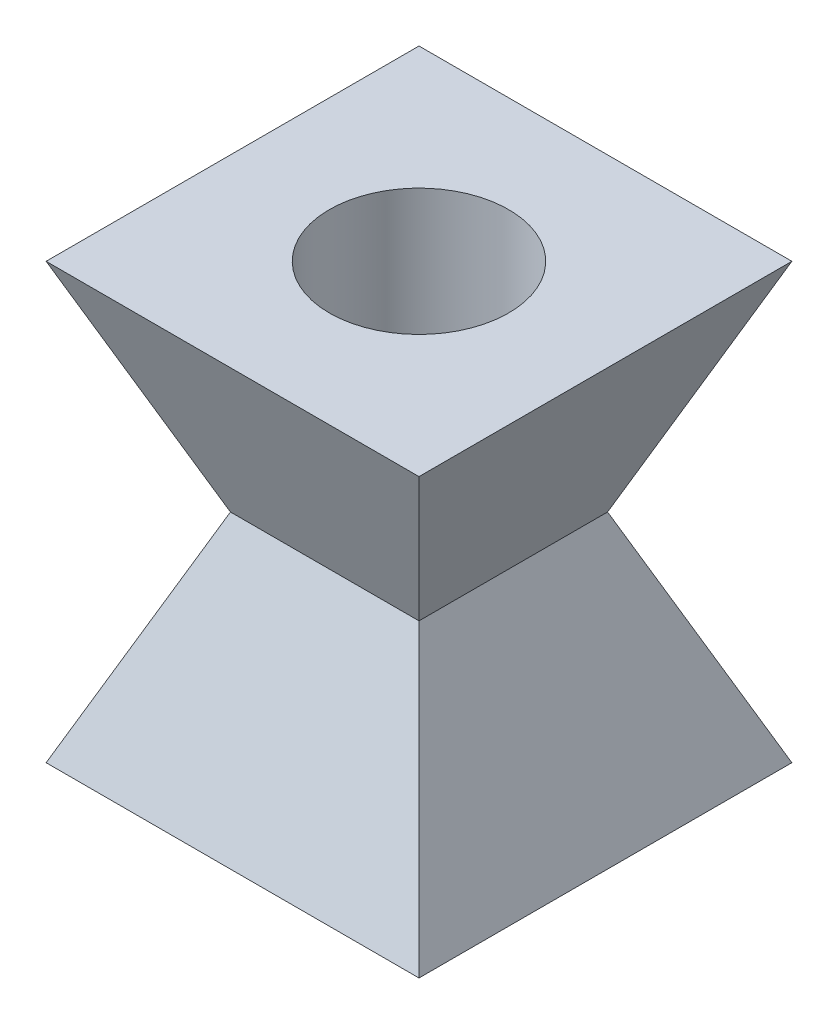
SolidWorks part; units mm, degrees
material "Cast Stainless Steel"
ref_plane "Front Plane" through (0, 0, 0) normal (0, 0, 1) x (1, 0, 0)
ref_plane "Top Plane" through (0, 0, 0) normal (0, 1, 0) x (1, 0, 0)
ref_plane "Right Plane" through (0, 0, 0) normal (1, 0, 0) x (0, 0, -1)
sketch "Sketch1" plane through (0, 0, 0) normal (0, 0, 1) x (1, 0, 0)
  line L1 (0, 0) -> (104, 0)
  line L2 (0, 0) -> (0, 121.1121)
  line L3 (0, 121.1121) -> (104, 121.1121)
  line L4 (104, 0) -> (104, 121.1121)
  dimension "D1" = 104
  dimension "D2" = 121.1121
extrude "Boss-Extrude1" add sketch "Sketch1" along normal blind 104
sketch "Sketch2" plane through (0, 0, 0) normal (0, 0, -1) x (-1, 0, 0)
  line L3 (0, 121.1121) -> (-25.7045, 60.556)
  line L4 (-25.7045, 60.556) -> (0, 0)
  line L5 (0, 0) -> (0, 121.1121)
  dimension "D1" = 23
extrude "Cut-Extrude1" cut sketch "Sketch2" against normal blind 104
sketch "Sketch3" plane through (0, 0, 0) normal (0, 0, -1) x (-1, 0, 0)
  line L2 (-104, 121.1121) -> (-78.2955, 60.556)
  line L3 (-78.2955, 60.556) -> (-104, 0)
  line L4 (-104, 0) -> (-104, 121.1121)
  dimension "D1" = 23
extrude "Cut-Extrude2" cut sketch "Sketch3" against normal blind 104
sketch "Sketch4" plane through (0, 0, 0) normal (1, 0, 0) x (0, 0, -1)
  line L0 (-104, 121.1121) -> (-78.2955, 60.556)
  line L1 (-104, 60.556) -> (0, 60.556) construction
  line L2 (-78.2955, 60.556) -> (-104, 0)
  line L3 (-104, 0) -> (-104, 121.1121)
  dimension "D1" = 23
extrude "Cut-Extrude3" cut sketch "Sketch4" along normal through all
sketch "Sketch5" plane through (0, 0, 0) normal (1, 0, 0) x (0, 0, -1)
  line L0 (0, 121.1121) -> (-25.7045, 60.556)
  line L1 (-78.2955, 60.556) -> (0, 60.556) construction
  line L2 (-25.7045, 60.556) -> (0, 0)
  line L3 (0, 0) -> (0, 121.1121)
  dimension "D1" = 23
extrude "Cut-Extrude4" cut sketch "Sketch5" along normal through all
sketch "Sketch6" plane through (0, 121.1121, 0) normal (0, 1, 0) x (1, 0, 0)
  circle A0 centre (52, -52) radius 25
  dimension "D1" = 50
extrude "Cut-Extrude5" cut sketch "Sketch6" against normal through all
equation "\"A\"= 115.00"
equation "\"B\"= 104.00"
equation "\"C\"= 23.00"
